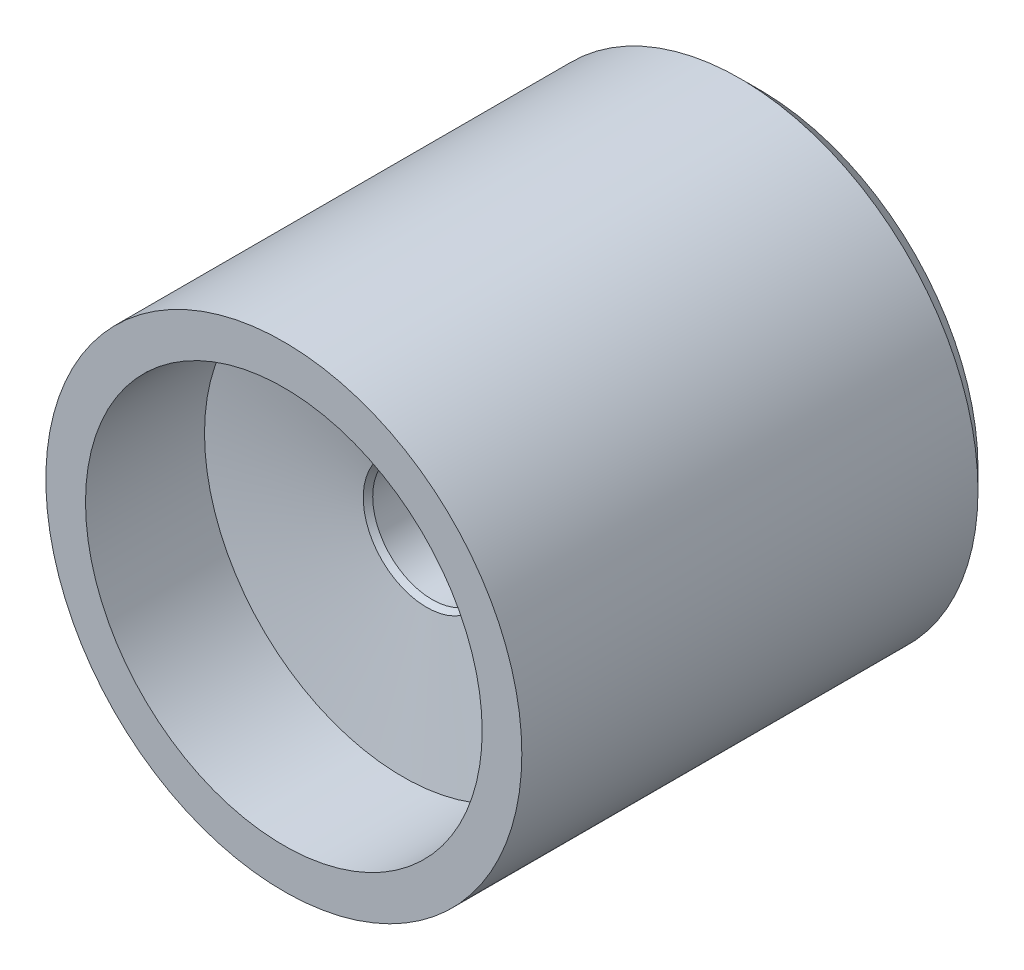
SolidWorks part; units mm, degrees
ref_plane "Front Plane" through (0, 0, 0) normal (0, 0, 1) x (1, 0, 0)
ref_plane "Top Plane" through (0, 0, 0) normal (0, 1, 0) x (1, 0, 0)
ref_plane "Right Plane" through (0, 0, 0) normal (1, 0, 0) x (0, 0, -1)
sketch "Sketch2" plane through (0, 0, 0) normal (0, 0, 1) x (1, 0, 0)
  circle A0 centre (0, 0) radius 6
  dimension "D1" = 12
extrude "Boss-Extrude1" add sketch "Sketch2" along normal blind 12
sketch "Sketch3" plane through (0, 0, 0) normal (0, 1, 0) x (1, 0, 0)
  line L0 (0, -12) -> (0, -3.5)
  line L1 (-6, -12) -> (6, -12) construction
  line L2 (0, -3.5) -> (1.5, -3.5)
  line L3 (1.5, -3.5) -> (1.5, -8.3829)
  line L4 (1.5, -8.3829) -> (5, -9)
  line L5 (5, -9) -> (5, -12)
  line L6 (5, -12) -> (0, -12)
  dimension "D1" = 8.5
  dimension "D2" = 1.5
  dimension "D3" = 80
  dimension "D4" = 3
  dimension "D5" = 5
revolve "Cut-Revolve1" cut sketch "Sketch3" angle 360 about L0
chamfer "Chamfer1" distance 0.1 angle 45 1 edges at (1.5, 0, 8.3829)
chamfer "Chamfer2" distance 0.5 angle 45 1 edges at (6, 0, 0)
